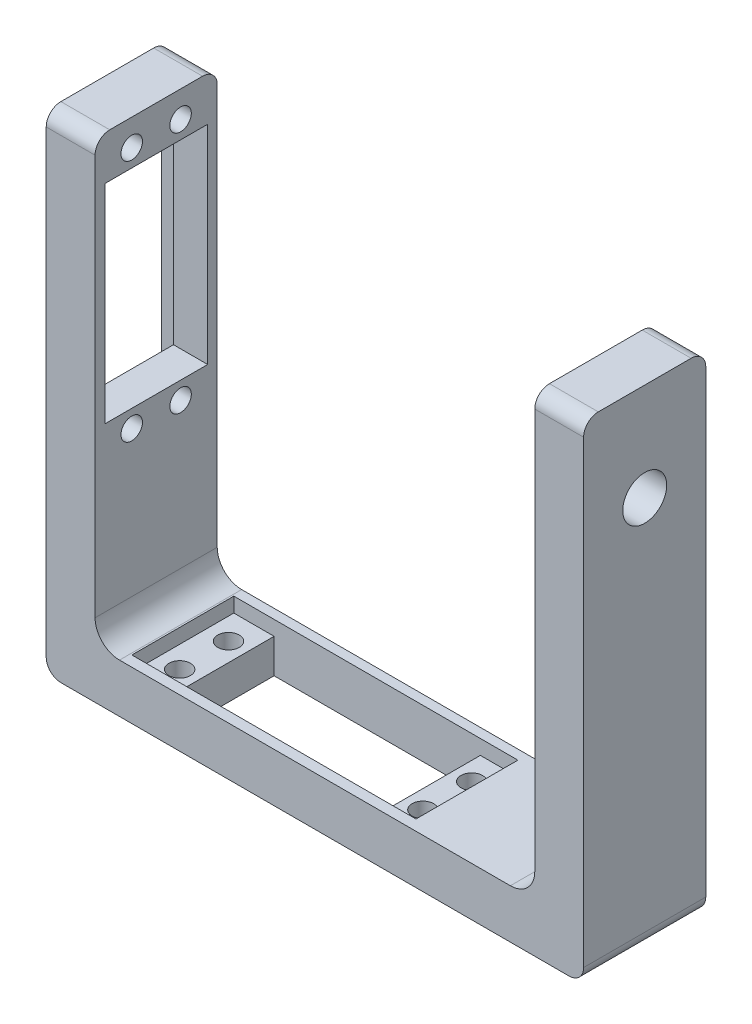
SolidWorks part; units mm, degrees
ref_plane "Ön Düzlem" through (0, 0, 0) normal (0, 0, 1) x (1, 0, 0)
ref_plane "Üst Düzlem" through (0, 0, 0) normal (0, 1, 0) x (1, 0, 0)
ref_plane "Sağ Düzlem" through (0, 0, 0) normal (1, 0, 0) x (0, 0, -1)
sketch "Sketch1" plane through (0, 0, 0) normal (0, 0, 1) x (1, 0, 0)
  line L1 (0, 0) -> (110, 0)
  line L2 (0, 0) -> (0, 100)
  line L3 (0, 100) -> (110, 100)
  line L4 (110, 0) -> (110, 100)
  line L5 (10, 100) -> (100, 100)
  line L6 (10, 100) -> (10, 10)
  line L7 (10, 10) -> (100, 10)
  line L8 (100, 100) -> (100, 10)
  dimension "D1" = 100
  dimension "D2" = 110
  dimension "D3" = 10
  dimension "D4" = 10
  dimension "D5" = 10
extrude "Boss-Extrude1" add sketch "Sketch1" along normal blind 25 contours L3 L8 L7 L6 L2 L1 L4
sketch "Sketch2" plane through (0, 0, 0) normal (-1, 0, 0) x (0, 0, 1)
  circle A0 centre (7.5, 94.5896) radius 2.2
  circle A1 centre (17.5, 94.5896) radius 2.2
  circle A2 centre (7.5, 44.8104) radius 2.2
  circle A3 centre (17.5, 44.8104) radius 2.2
extrude "Cut-Extrude1" cut sketch "Sketch2" against normal blind 10
ref_plane "Plane1" through (10, 10, 0) normal (0, 0, -1) x (-1, 0, 0)
sketch "Sketch4" plane through (10, 0, 0) normal (1, 0, 0) x (0, 0, -1)
  line L1 (-22.9689, 90.9651) -> (-1.9486, 90.9651)
  line L2 (-22.9689, 90.9651) -> (-22.9689, 48.3741)
  line L3 (-22.9689, 48.3741) -> (-1.9486, 48.3741)
  line L4 (-1.9486, 90.9651) -> (-1.9486, 48.3741)
extrude "Cut-Extrude2" cut sketch "Sketch4" against normal blind 14
sketch "Sketch5" plane through (0, 0, 0) normal (-1, 0, 0) x (0, 0, 1)
  line L1 (1.3587, 98.1026) -> (24.0244, 98.1026)
  line L2 (1.3587, 98.1026) -> (1.3587, 40.6477)
  line L3 (1.3587, 40.6477) -> (24.0244, 40.6477)
  line L4 (24.0244, 98.1026) -> (24.0244, 40.6477)
extrude "Cut-Extrude3" cut sketch "Sketch5" against normal blind 3
fillet "Fillet1" radius 5 2 edges at (100, 10, 12.5) (10, 10, 12.5)
fillet "Fillet2" radius 3 6 edges at (105, 100, 0) (105, 100, 25) (5, 100, 0) (5, 100, 25) (110, 0, 12.5) (0, 0, 12.5)
sketch "Sketch6" plane through (110, 0, 0) normal (1, 0, 0) x (0, 0, -1)
  circle A0 centre (-12.5, 80) radius 4.5
  circle A1 centre (-12.5, 80) radius 4 construction
  dimension "D1" = 9
extrude "Cut-Extrude4" cut sketch "Sketch6" against normal blind 10
sketch "Sketch7" plane through (0, 0, 0) normal (0, -1, 0) x (-1, 0, 0)
  line L0 (-3, -25) -> (-107, -25) construction
  line L1 (-3, -25) -> (-3, 0) construction
  circle A0 centre (-55, -12.5) radius 3.2978
  point P5 (-55, -25)
  point P9 (-3, -12.5)
sketch "Sketch8" plane through (0, 0, 0) normal (0, -1, 0) x (1, 0, 0)
  line L1 (23.6076, 22.8338) -> (65.8224, 22.8338)
  line L2 (23.6076, 22.8338) -> (23.6076, 1.9637)
  line L3 (23.6076, 1.9637) -> (65.8224, 1.9637)
  line L4 (65.8224, 22.8338) -> (65.8224, 1.9637)
extrude "Cut-Extrude5" cut sketch "Sketch8" against normal blind 21
sketch "Sketch9" plane through (0, 10, 0) normal (0, 1, 0) x (1, 0, 0)
  line L0 (23.6076, -22.8338) -> (65.8224, -22.8338) construction
  line L1 (15.3609, -1.9637) -> (73.5084, -1.9637)
  line L2 (15.3609, -1.9637) -> (15.3609, -22.8338)
  line L3 (15.3609, -22.8338) -> (73.5084, -22.8338)
  line L4 (73.5084, -1.9637) -> (73.5084, -22.8338)
  line L5 (65.8224, -1.9637) -> (23.6076, -1.9637) construction
extrude "Cut-Extrude6" cut sketch "Sketch9" against normal blind 3
sketch "Sketch10" plane through (0, 7, 0) normal (0, 1, 0) x (1, 0, 0)
  circle A0 centre (69.5896, -7.5) radius 2.2
  circle A1 centre (69.5896, -17.5) radius 2.2
  circle A2 centre (19.8104, -7.5) radius 2.2
  circle A3 centre (19.8104, -17.5) radius 2.2
extrude "Cut-Extrude7" cut sketch "Sketch10" against normal blind 23
